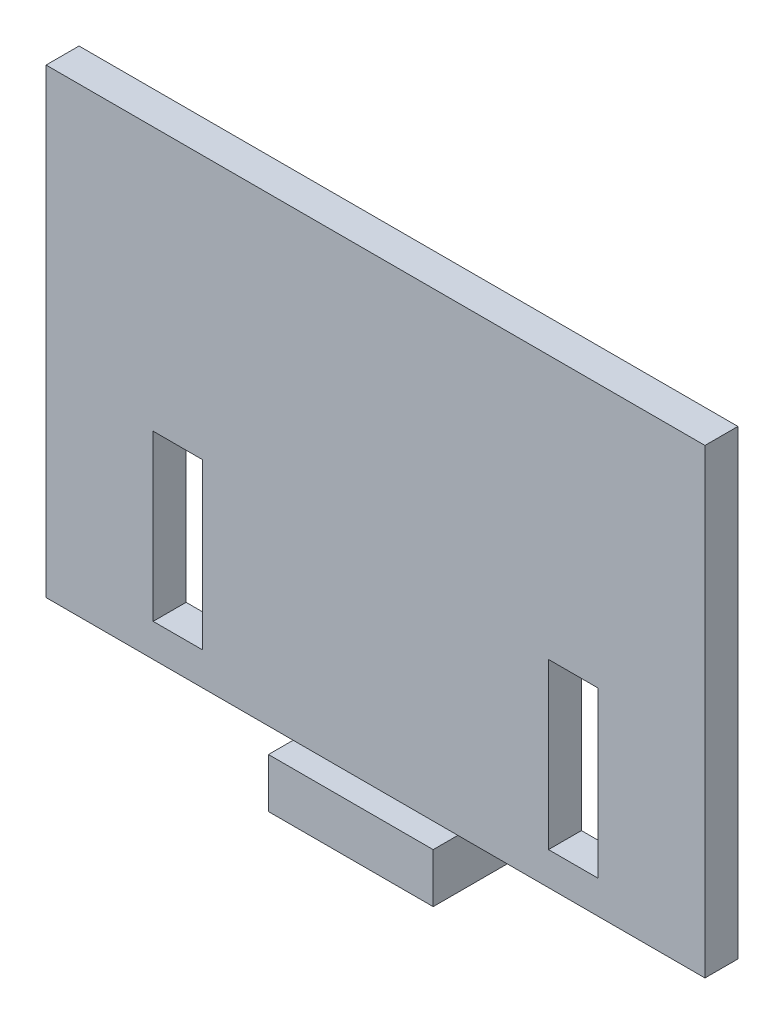
SolidWorks part; units mm, degrees
ref_plane "Front Plane" through (0, 0, 0) normal (0, 0, 1) x (1, 0, 0)
ref_plane "Top Plane" through (0, 0, 0) normal (0, 1, 0) x (1, 0, 0)
ref_plane "Right Plane" through (0, 0, 0) normal (1, 0, 0) x (0, 0, -1)
sketch "Sketch1" plane through (0, 0, 0) normal (0, 0, 1) x (1, 0, 0)
  line L1 (-20, 14) -> (20, 14)
  line L2 (-20, 14) -> (-20, -14)
  line L3 (-20, -14) -> (20, -14)
  line L4 (20, 14) -> (20, -14)
  line L5 (-20, 14) -> (20, -14) construction
  line L6 (-20, -14) -> (20, 14) construction
  point P0 (0, 0)
  dimension "D1" = 40
  dimension "D2" = 28
extrude "Boss-Extrude1" add sketch "Sketch1" along normal blind 2
sketch "Sketch2" plane through (0, 0, 2) normal (0, 0, 1) x (1, 0, 0)
  line L0 (0, -14) -> (0, -7) construction
  line L1 (-20, -14) -> (20, -14) construction
  line L2 (0, -7) -> (12, -7) construction
  line L3 (0, -7) -> (-12, -7) construction
  line L4 (-12, -14) -> (-12, -12) construction
  line L5 (-13.5, -2) -> (-10.5, -2)
  line L6 (-13.5, -2) -> (-13.5, -12)
  line L7 (-13.5, -12) -> (-10.5, -12)
  line L8 (-10.5, -2) -> (-10.5, -12)
  line L9 (-13.5, -2) -> (-10.5, -12) construction
  line L10 (-13.5, -12) -> (-10.5, -2) construction
  line L11 (10.5, -2) -> (13.5, -2)
  line L12 (10.5, -2) -> (10.5, -12)
  line L13 (10.5, -12) -> (13.5, -12)
  line L14 (13.5, -2) -> (13.5, -12)
  line L15 (10.5, -2) -> (13.5, -12) construction
  line L16 (10.5, -12) -> (13.5, -2) construction
  dimension "D1" = 12
  dimension "D2" = 12
  dimension "D3" = 3
  dimension "D4" = 2
  dimension "10mm" = 10
  dimension "D5" = 3
  dimension "D6" = 10
extrude "Cut-Extrude1" cut sketch "Sketch2" against normal through all both and the other way through all
sketch "Sketch5" plane through (0, -14, 0) normal (0, -1, 0) x (-1, 0, 0)
  line L0 (0, 0) -> (0, -2) construction
  line L1 (20, -2) -> (-20, -2) construction
  line L3 (5, -3.5) -> (-5, -3.5)
  line L4 (5, -3.5) -> (5, 1.5)
  line L5 (5, 1.5) -> (-5, 1.5)
  line L6 (-5, -3.5) -> (-5, 1.5)
  line L7 (5, -3.5) -> (-5, 1.5) construction
  line L8 (5, 1.5) -> (-5, -3.5) construction
  point P5 (0, -1)
  dimension "D1" = 10
  dimension "D2" = 5
extrude "Boss-Extrude2" add sketch "Sketch5" along normal blind 3
